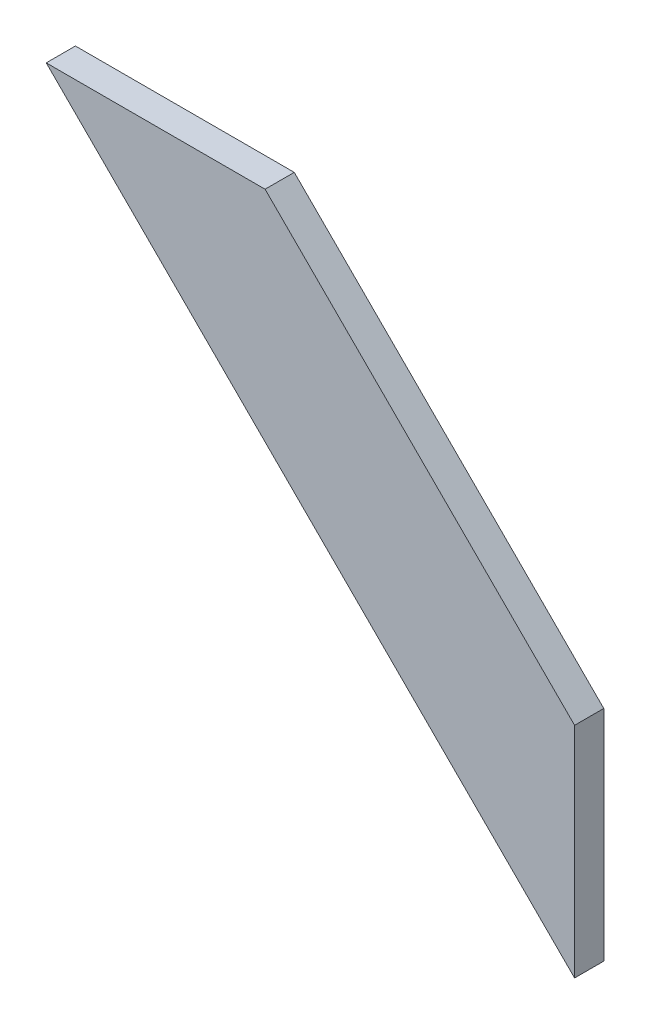
SolidWorks part; units mm, degrees
material "AISI 304"
ref_plane "前视基准面" through (0, 0, 0) normal (0, 0, 1) x (1, 0, 0)
ref_plane "上视基准面" through (0, 0, 0) normal (0, 1, 0) x (1, 0, 0)
ref_plane "右视基准面" through (0, 0, 0) normal (1, 0, 0) x (0, 0, -1)
sketch "Sketch1" plane through (0, 0, 0) normal (0, 0, 1) x (1, 0, 0)
  line L0 (0, 0) -> (15, 0)
  line L1 (15, 0) -> (36.2132, -21.2132)
  line L2 (36.2132, -21.2132) -> (36.2132, -36.2132)
  line L3 (36.2132, -36.2132) -> (0, 0)
  dimension "D1" = 15
  dimension "D2" = 15
  dimension "D3" = 135
  dimension "D4" = 30
extrude "Boss-Extrude1" add sketch "Sketch1" along normal blind 2
